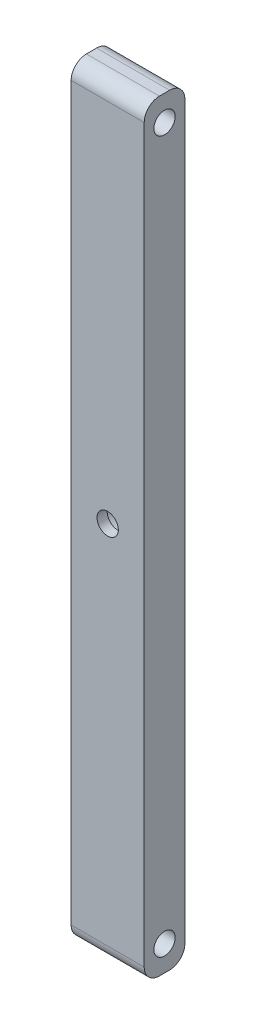
SolidWorks part; units mm, degrees
ref_plane "Alzado" through (0, 0, 0) normal (0, 0, 1) x (1, 0, 0)
ref_plane "Planta" through (0, 0, 0) normal (0, 1, 0) x (1, 0, 0)
ref_plane "Vista lateral" through (0, 0, 0) normal (1, 0, 0) x (0, 0, -1)
sketch "Croquis1" plane through (0, 0, -134.1989) normal (0, 0, -1) x (-1, 0, 0)
  line L0 (-57.7153, 173.4478) -> (-47.7153, 173.4478) construction
  line L1 (-57.7153, 173.4478) -> (-57.7153, 153.4478) construction
  line L2 (-47.7153, 153.4478) -> (-47.7153, 173.4478) construction
  line L3 (-57.7153, 153.4478) -> (-47.7153, 153.4478) construction
  line L4 (-57.7153, 173.4478) -> (-47.7153, 173.4478)
  line L5 (-57.7153, 173.4478) -> (-57.7153, 153.4478)
  line L6 (-47.7153, 153.4478) -> (-47.7153, 173.4478)
  line L7 (-57.7153, 153.4478) -> (-47.7153, 153.4478)
  line L9 (-59.9068, 88.4478) -> (-45.5239, 88.4478)
  line L10 (-59.9068, 88.4478) -> (-59.9068, 238.4478)
  line L11 (-59.9068, 238.4478) -> (-45.5239, 238.4478)
  line L12 (-45.5239, 88.4478) -> (-45.5239, 238.4478)
  line L13 (-59.9068, 88.4478) -> (-45.5239, 238.4478) construction
  line L14 (-59.9068, 238.4478) -> (-45.5239, 88.4478) construction
  circle A0 centre (-52.7153, 163.4478) radius 3.1 construction
  circle A1 centre (-52.7153, 163.4478) radius 3.1
  circle A4 centre (-52.7153, 163.4478) radius 2.1
  circle M11 centre (-52.7153, 163.4478) radius 3.1
  line M12 (-47.7153, 173.4478) -> (-57.7153, 173.4478)
  line M13 (-57.7153, 173.4478) -> (-57.7153, 153.4478)
  line M14 (-57.7153, 153.4478) -> (-47.7153, 153.4478)
  line M15 (-47.7153, 153.4478) -> (-47.7153, 173.4478)
  dimension "D1" = 4.2
  dimension "D2" = 150
extrude "Saliente-Extruir1" add sketch "Croquis1" along normal blind 2 contours L9 L12 L11 L10 M12 M15 M14 M13 | M15 M12 M13 M14 M11 | A4 M11
sketch "Croquis2" plane through (0, 0, -136.1989) normal (0, 0, -1) x (-1, 0, 0)
  line L4 (-59.9068, 88.4478) -> (-45.5239, 88.4478)
  line L5 (-45.5239, 88.4478) -> (-45.5239, 238.4478)
  line L6 (-45.5239, 238.4478) -> (-59.9068, 238.4478)
  line L7 (-59.9068, 238.4478) -> (-59.9068, 88.4478)
  line L8 (-59.9068, 88.4478) -> (-45.5239, 88.4478)
  line L9 (-45.5239, 88.4478) -> (-45.5239, 238.4478)
  line L10 (-45.5239, 238.4478) -> (-59.9068, 238.4478)
  line L11 (-59.9068, 238.4478) -> (-59.9068, 88.4478)
  circle A0 centre (-52.7153, 163.4478) radius 4
  dimension "D2" = 8
  dimension "D1" = 0
extrude "Saliente-Extruir2" add sketch "Croquis2" along normal blind 6
sketch "Croquis3" plane through (45.5239, 0, 0) normal (-1, 0, 0) x (0, 0, 1)
  line L4 (-134.1989, 88.4478) -> (-134.1989, 238.4478)
  line L5 (-134.1989, 238.4478) -> (-142.1989, 238.4478)
  line L6 (-142.1989, 238.4478) -> (-142.1989, 88.4478)
  line L7 (-142.1989, 88.4478) -> (-134.1989, 88.4478)
  line L8 (-134.1989, 88.4478) -> (-134.1989, 238.4478)
  line L9 (-134.1989, 238.4478) -> (-142.1989, 238.4478)
  line L10 (-142.1989, 238.4478) -> (-142.1989, 88.4478)
  line L11 (-142.1989, 88.4478) -> (-134.1989, 88.4478)
  circle A0 centre (-138.1989, 233.4478) radius 3.1
  circle A1 centre (-138.1989, 93.4478) radius 3.1
  point P8 (-138.1989, 93.4478)
  dimension "D4" = 6.2
  dimension "D2" = 5
  dimension "D3" = 4
  dimension "D5" = 5
  dimension "D1" = 0
extrude "Cortar-Extruir1" cut sketch "Croquis3" against normal blind 4 contours A1 | A0
sketch "Croquis4" plane through (49.5239, 0, 0) normal (-1, 0, 0) x (0, 0, 1)
  circle A0 centre (-138.1989, 233.4478) radius 2.1
  circle A1 centre (-138.1989, 93.4478) radius 3.1
  circle A2 centre (-138.1989, 93.4478) radius 3.1
  circle A3 centre (-138.1989, 233.4478) radius 3.1
  circle A4 centre (-138.1989, 233.4478) radius 3.1
  circle A5 centre (-138.1989, 93.4478) radius 2.1
  dimension "D3" = 4.2
  dimension "D1" = 0
  dimension "D2" = 0
extrude "Cortar-Extruir2" cut sketch "Croquis4" against normal through all contours A0 | A5
fillet "Redondeo2" radius 3 4 edges at (52.7153, 238.4478, -134.1989) (52.7153, 238.4478, -142.1989) (52.7153, 88.4478, -134.1989) (52.7153, 88.4478, -142.1989)
